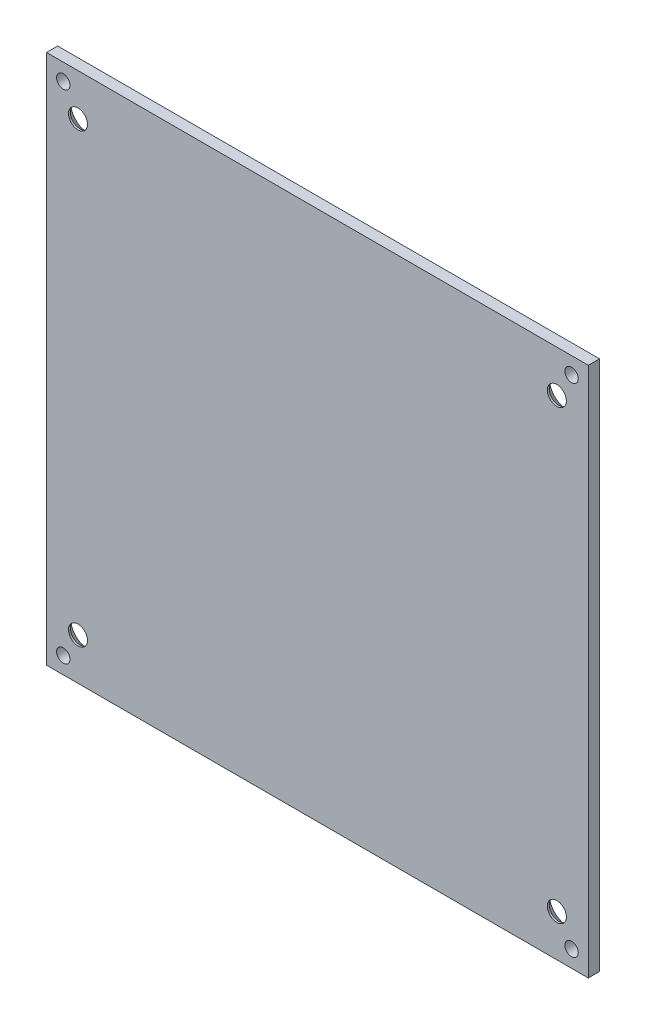
SolidWorks part; units mm, degrees
material "6061-T6 (SS)"
ref_plane "Front Plane" through (0, 0, 0) normal (0, 0, 1) x (1, 0, 0)
ref_plane "Top Plane" through (0, 0, 0) normal (0, 1, 0) x (1, 0, 0)
ref_plane "Right Plane" through (0, 0, 0) normal (1, 0, 0) x (0, 0, -1)
sketch "Plate sketch" plane through (0, 0, 0) normal (0, 0, 1) x (1, 0, 0)
  line L1 (0, 0) -> (97, 0)
  line L2 (0, 0) -> (0, 95)
  line L3 (0, 95) -> (97, 95)
  line L4 (97, 0) -> (97, 95)
  dimension "D1" = 97
  dimension "D2" = 95
extrude "Plate" add sketch "Plate sketch" along normal blind 2
sketch "M2 foot screw holes sketch" plane through (0, 0, 0) normal (0, 0, 1) x (1, 0, 0)
  circle A0 centre (3, 3) radius 1.2
  circle A1 centre (94, 3) radius 1.2
  circle A2 centre (3, 92) radius 1.2
  circle A3 centre (94, 92) radius 1.2
extrude "M2 foot screw holes" cut sketch "M2 foot screw holes sketch" against normal through all and the other way through all
sketch "M3 stack rod holes sketch" plane through (0, 0, 0) normal (0, 0, 1) x (1, 0, 0)
  circle A0 centre (5.635, 7.495) radius 1.7
  circle A1 centre (91.365, 7.495) radius 1.7
  circle A2 centre (5.635, 87.505) radius 1.7
  circle A3 centre (91.365, 87.505) radius 1.7
extrude "M3 stack rod holes" cut sketch "M3 stack rod holes sketch" against normal through all and the other way through all
chamfer "M3 countersinks" distance 1.66 angle 45 4 edges at (3.935, 7.495, 0) (89.665, 87.505, 0) (3.935, 87.505, 0) (89.665, 7.495, 0)
